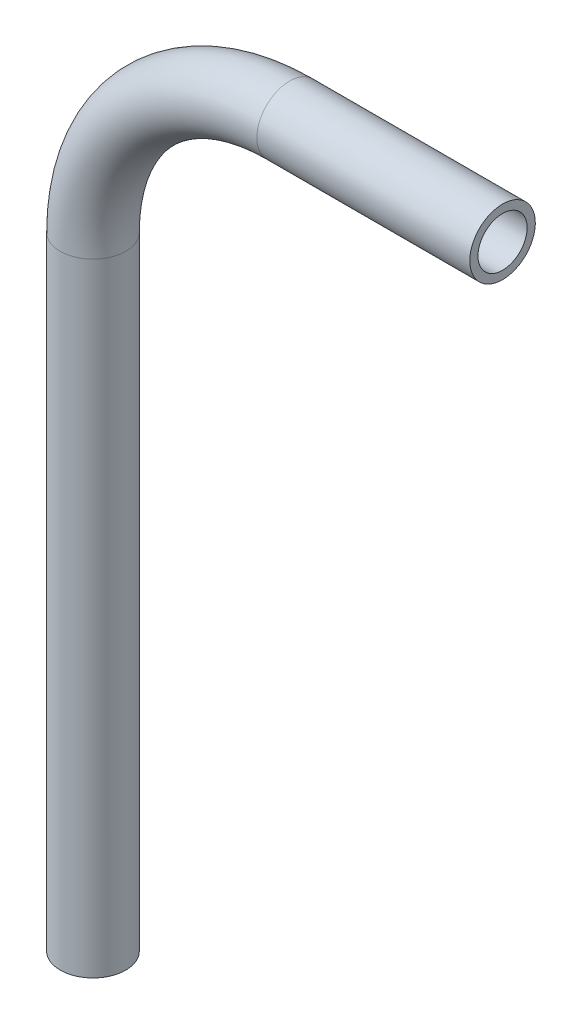
SolidWorks part; units mm, degrees
ref_plane "Front Plane" through (0, 0, 0) normal (0, 0, 1) x (1, 0, 0)
ref_plane "Top Plane" through (0, 0, 0) normal (0, 1, 0) x (1, 0, 0)
ref_plane "Right Plane" through (0, 0, 0) normal (1, 0, 0) x (0, 0, -1)
sketch "Sketch1" plane through (0, 0, 0) normal (0, 0, 1) x (1, 0, 0)
  line L0 (0, 0) -> (0, 76)
  line L1 (24, 100) -> (50, 100)
  arc A0 (0, 76) -> (24, 100) centre (24, 76) cw
  point P6 (0, 100)
  dimension "D3" = 24
  dimension "D1" = 100
  dimension "D2" = 50
  dimension "D4" = 90
sketch "Sketch2" plane through (0, 0, 0) normal (0, 1, 0) x (1, 0, 0)
  circle A0 centre (0, 0) radius 4
  circle A1 centre (0, 0) radius 3
  dimension "D1" = 6
  dimension "D2" = 8
sweep "Sweep1" add profiles "Sketch2" path "Sketch1"
